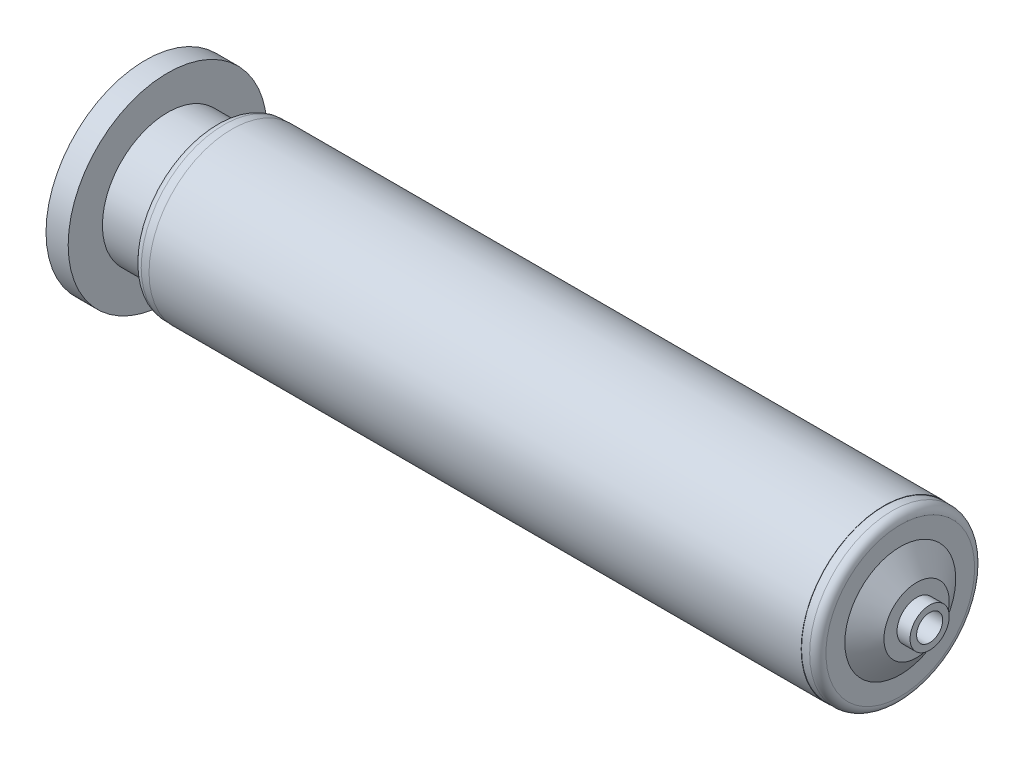
SolidWorks part; units mm, degrees
ref_plane "Front Plane" through (0, 0, 0) normal (0, 0, 1) x (1, 0, 0)
ref_plane "Top Plane" through (0, 0, 0) normal (0, 1, 0) x (1, 0, 0)
ref_plane "Right Plane" through (0, 0, 0) normal (1, 0, 0) x (0, 0, -1)
sketch "Sketch1" plane through (0, 0, 0) normal (0, 1, 0) x (1, 0, 0)
  line L0 (-127.5, 0) -> (127.5, 0)
  line L1 (127.5, 0) -> (127.5, -6)
  line L2 (127.5, -6) -> (123.5, -6)
  line L4 (118.5, -17) -> (118.5, -25.3)
  line L5 (118.5, -25.3) -> (113.5, -25.3)
  line L6 (113.5, -25.3) -> (113.5, -25.4)
  line L7 (113.5, -25.4) -> (-86.5, -25.4)
  line L8 (-86.5, -25.4) -> (-86.5, -25.3)
  line L9 (-86.5, -25.3) -> (-91.5, -25.3)
  line L10 (-91.5, -25.3) -> (-91.5, -20)
  line L11 (-91.5, -20) -> (-106.2, -20)
  line L12 (-106.2, -20) -> (-106.2, -30.5)
  line L13 (-106.2, -30.5) -> (-113, -30.5)
  line L14 (-113, -30.5) -> (-113, -18.75)
  line L15 (-113, -18.75) -> (-118.5, -18.75)
  line L17 (-123.5, -6) -> (-127.5, -6)
  line L18 (-127.5, -6) -> (-127.5, 0)
  line L19 (-123.5, -6) -> (-123.5, -10)
  line L21 (118.5, -17) -> (123.5, -10)
  line L22 (123.5, -10) -> (123.5, -6)
  line L23 (-123.5, -10) -> (123.5, -10) construction
  line L24 (-123.5, -10) -> (-118.5, -17)
  line L25 (-118.5, -17) -> (-118.5, -18.75)
  line L26 (-118.5, -17) -> (118.5, -17) construction
  point P16 (-123.5, -8)
  dimension "D1" = 255
  dimension "D2" = 6
  dimension "D3" = 25.4
  dimension "D4" = 0.1
  dimension "D5" = 0.1
  dimension "D6" = 10
  dimension "D7" = 5
  dimension "D8" = 5
  dimension "D9" = 17
  dimension "D10" = 4
  dimension "D11" = 247
  dimension "D12" = 200
  dimension "D13" = 5
  dimension "D14" = 6.8
  dimension "D15" = 5.5
  dimension "D16" = 18.75
  dimension "D17" = 30.5
  dimension "D18" = 20
revolve "Revolve1" add sketch "Sketch1" angle 360 about L0
sketch "Sketch3" plane through (0, 0, 0) normal (1, 0, 0) x (0, 0, -1)
  circle A0 centre (0, 0) radius 4
  dimension "D1" = 8
extrude "Cut-Extrude1" cut sketch "Sketch3" against normal through all both and the other way through all
fillet "Fillet1" radius 2.5 2 edges at (118.5, 0, 25.3) (-91.5, 0, 25.3)
